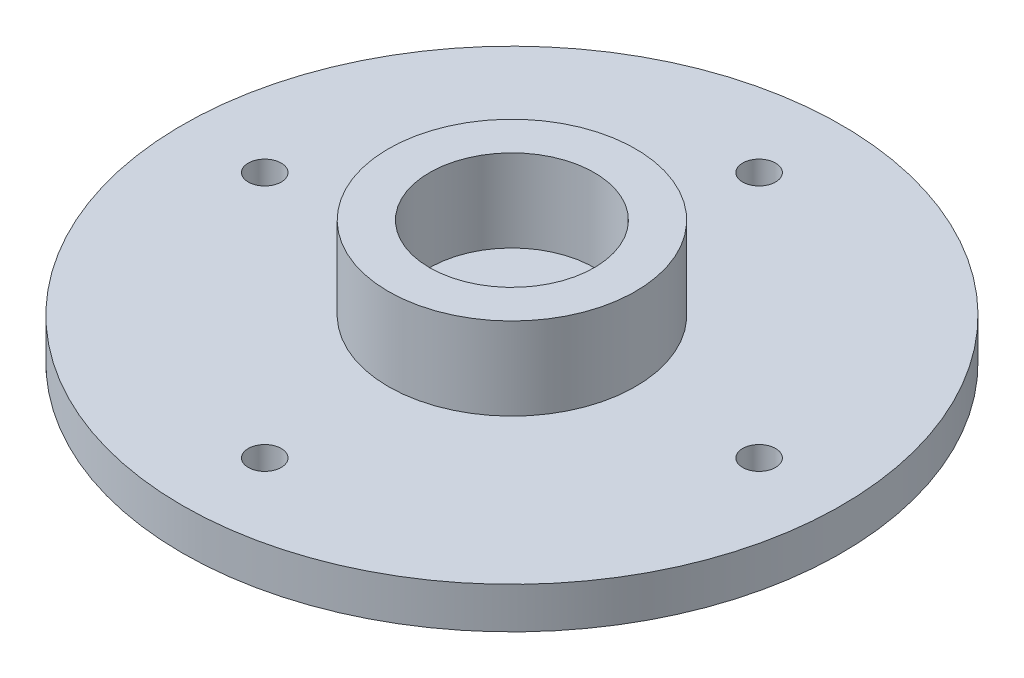
SolidWorks part; units mm, degrees
ref_plane "Front Plane" through (0, 0, 0) normal (0, 0, 1) x (1, 0, 0)
ref_plane "Top Plane" through (0, 0, 0) normal (0, 1, 0) x (1, 0, 0)
ref_plane "Right Plane" through (0, 0, 0) normal (1, 0, 0) x (0, 0, -1)
sketch "Sketch1" plane through (0, 0, 0) normal (0, 1, 0) x (1, 0, 0)
  line L0 (0, 0) -> (0, 30) construction
  circle A0 centre (0, 0) radius 40
  circle A1 centre (0, 0) radius 30 construction
  circle A2 centre (0, 30) radius 2
  circle A3 centre (30, 0) radius 2
  circle A4 centre (0, -30) radius 2
  circle A5 centre (-30, 0) radius 2
  dimension "D1" = 80
  dimension "D2" = 60
  dimension "D3" = 4
  dimension "D5" = 30
  dimension "D4" = 4
extrude "Boss-Extrude1" add sketch "Sketch1" along normal mid plane 5
sketch "Sketch2" plane through (0, 2.5, 0) normal (0, 1, 0) x (1, 0, 0)
  circle A0 centre (0, 0) radius 15
  circle A1 centre (0, 0) radius 10
  dimension "D1" = 30
  dimension "D2" = 20
extrude "Boss-Extrude2" add sketch "Sketch2" along normal blind 10 contours A0 | A1
